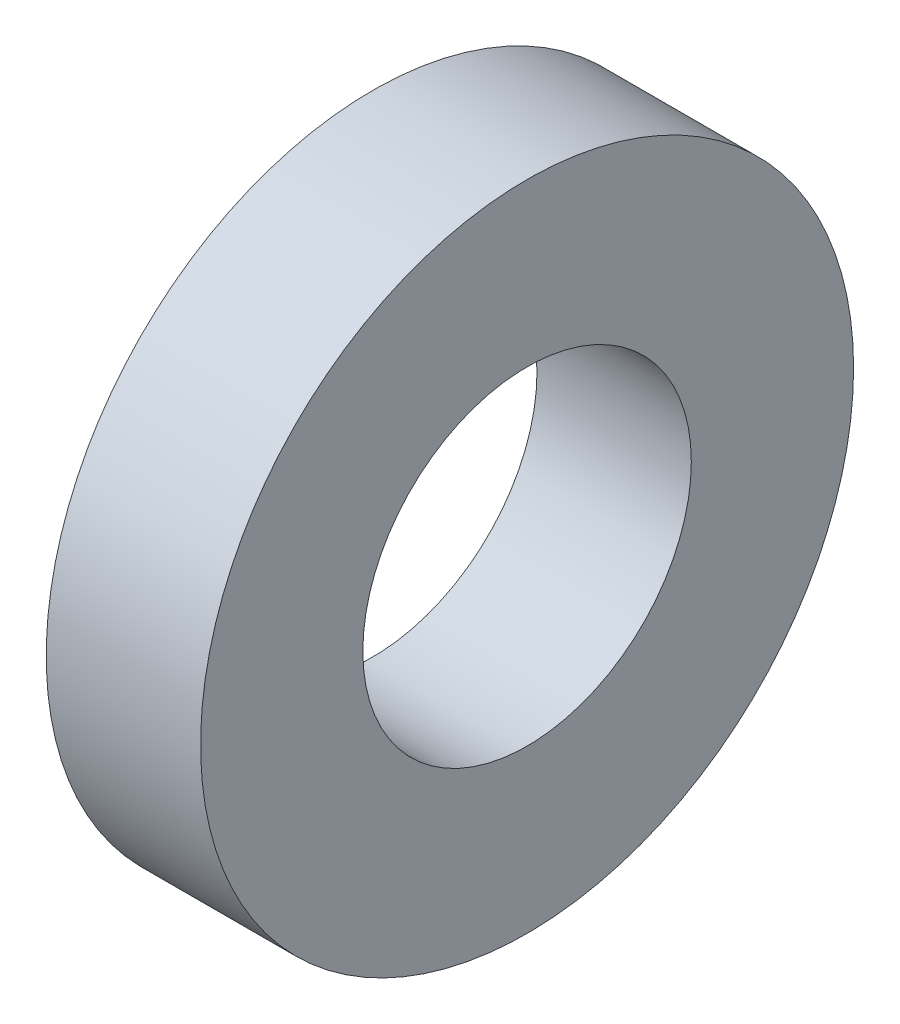
SolidWorks part; units mm, degrees
material "ABS"
ref_plane "前视基准面" through (0, 0, 0) normal (0, 0, 1) x (1, 0, 0)
ref_plane "上视基准面" through (0, 0, 0) normal (0, 1, 0) x (1, 0, 0)
ref_plane "右视基准面" through (0, 0, 0) normal (1, 0, 0) x (0, 0, -1)
other "Configuration Table"
sketch "草图1" plane through (0, 0, 0) normal (1, 0, 0) x (0, 0, -1)
  circle A0 centre (0, 0) radius 4.15
  circle A1 centre (0, 0) radius 8.25
  dimension "D1" = 8.3
  dimension "D2" = 16.5
extrude "凸台-拉伸1" add sketch "草图1" along normal blind 3.9
